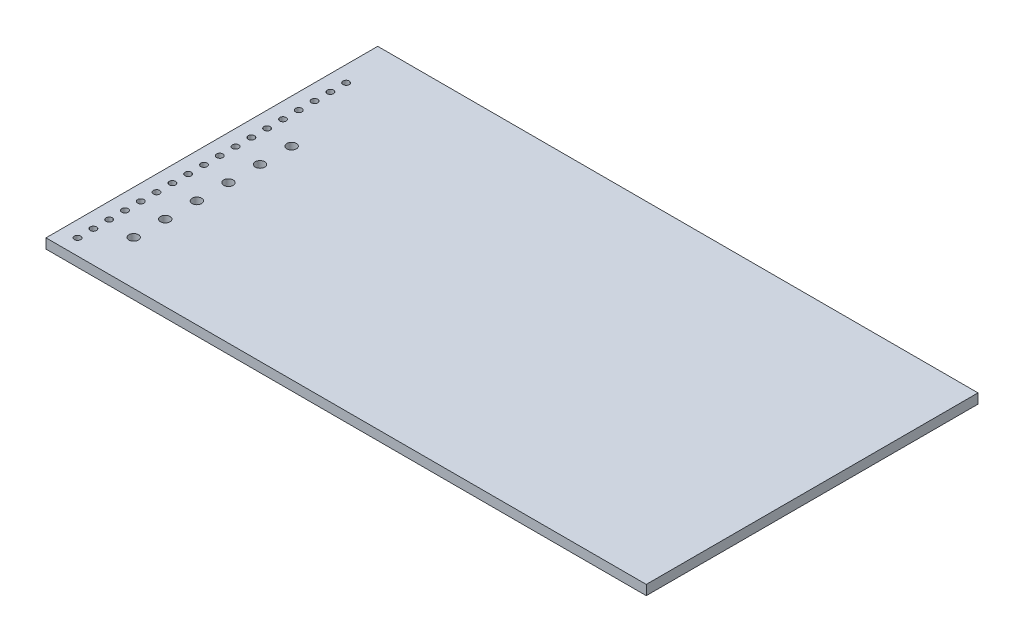
SolidWorks part; units mm, degrees
ref_plane "Front Plane" through (0, 0, 0) normal (0, 0, 1) x (1, 0, 0)
ref_plane "Top Plane" through (0, 0, 0) normal (0, 1, 0) x (1, 0, 0)
ref_plane "Right Plane" through (0, 0, 0) normal (1, 0, 0) x (0, 0, -1)
sketch "Sketch1" plane through (0, 0, 0) normal (0, 1, 0) x (1, 0, 0)
  line L1 (0, 0) -> (96.52, 0)
  line L2 (0, 0) -> (0, 53.34)
  line L3 (0, 53.34) -> (96.52, 53.34)
  line L4 (96.52, 0) -> (96.52, 53.34)
  dimension "D1" = 53.34
  dimension "D2" = 96.52
extrude "Boss-Extrude1" add sketch "Sketch1" along normal blind 1.5748
sketch "Sketch2" plane through (0, 1.5748, 0) normal (0, 1, 0) x (1, 0, 0)
  line L0 (2.54, 2.54) -> (2.54, 45.72) construction
  line L1 (0, 53.34) -> (0, 0) construction
  line L2 (0, 0) -> (96.52, 0) construction
  line L3 (6.985, 7.112) -> (6.985, 32.512) construction
  circle A0 centre (2.54, 2.54) radius 0.508
  circle A1 centre (2.54, 5.08) radius 0.508
  circle A2 centre (2.54, 7.62) radius 0.508
  circle A3 centre (2.54, 10.16) radius 0.508
  circle A4 centre (2.54, 12.7) radius 0.508
  circle A5 centre (2.54, 15.24) radius 0.508
  circle A6 centre (2.54, 17.78) radius 0.508
  circle A7 centre (2.54, 20.32) radius 0.508
  circle A8 centre (2.54, 22.86) radius 0.508
  circle A9 centre (2.54, 25.4) radius 0.508
  circle A10 centre (2.54, 27.94) radius 0.508
  circle A11 centre (2.54, 30.48) radius 0.508
  circle A12 centre (2.54, 33.02) radius 0.508
  circle A13 centre (2.54, 35.56) radius 0.508
  circle A14 centre (2.54, 38.1) radius 0.508
  circle A15 centre (2.54, 40.64) radius 0.508
  circle A16 centre (2.54, 43.18) radius 0.508
  circle A17 centre (2.54, 45.72) radius 0.508
  circle A18 centre (6.985, 7.112) radius 0.762
  circle A19 centre (6.985, 12.192) radius 0.762
  circle A20 centre (6.985, 17.272) radius 0.762
  circle A21 centre (6.985, 22.352) radius 0.762
  circle A22 centre (6.985, 27.432) radius 0.762
  circle A23 centre (6.985, 32.512) radius 0.762
  dimension "D3" = 1.016
  dimension "D9" = 1.524
  dimension "D1" = 2.54
  dimension "D2" = 2.54
  dimension "D4" = 43.18
  dimension "D6" = 25.4
  dimension "D7" = 6.985
  dimension "D8" = 7.112
  dimension "D5" = 18
  dimension "D10" = 6
extrude "Cut-Extrude1" cut sketch "Sketch2" against normal through all
